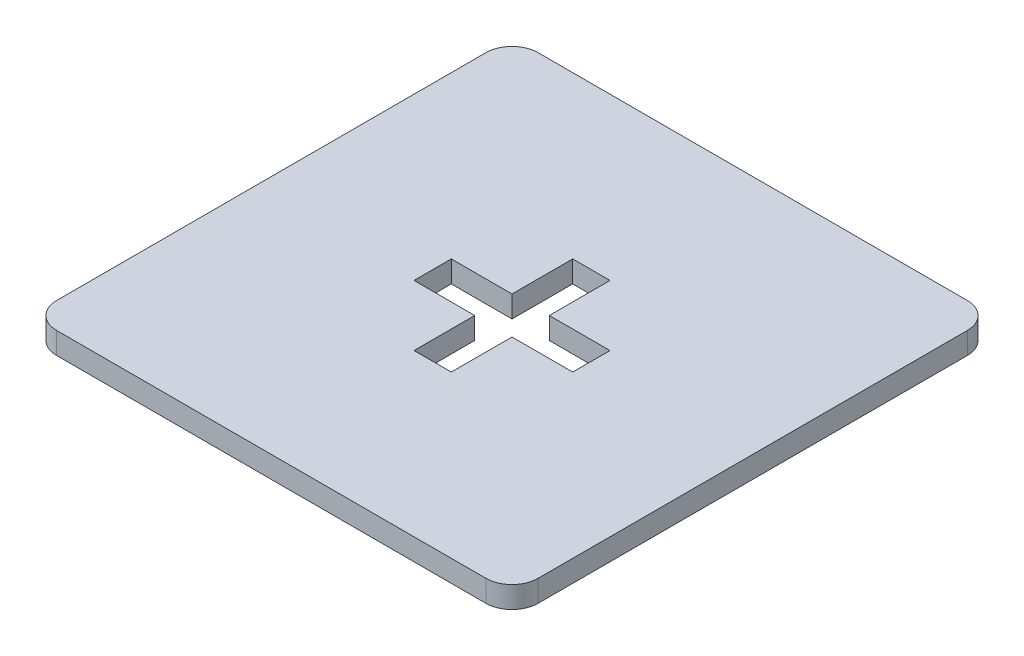
SolidWorks part; units mm, degrees
ref_plane "Plano frontal" through (0, 0, 0) normal (0, 0, 1) x (1, 0, 0)
ref_plane "Plano superior" through (0, 0, 0) normal (0, 1, 0) x (1, 0, 0)
ref_plane "Plano direito" through (0, 0, 0) normal (1, 0, 0) x (0, 0, -1)
sketch "Esboço1" plane through (0, 0, 0) normal (0, 1, 0) x (1, 0, 0)
  line L1 (-27.75, 27.75) -> (27.75, 27.75)
  line L2 (-27.75, 27.75) -> (-27.75, -27.75)
  line L3 (-27.75, -27.75) -> (27.75, -27.75)
  line L4 (27.75, 27.75) -> (27.75, -27.75)
  line L5 (-27.75, 27.75) -> (27.75, -27.75) construction
  line L6 (-27.75, -27.75) -> (27.75, 27.75) construction
  point P0 (0, 0)
  dimension "D1" = 55.5
  dimension "D2" = 55.5
extrude "Ressalto-extrusão1" add sketch "Esboço1" along normal blind 2.5
fillet "Filete1" radius 3 1 edges at (27.75, 1.25, -27.75)
fillet "Filete2" radius 3 1 edges at (-27.75, 1.25, -27.75)
fillet "Filete3" radius 3 1 edges at (-27.75, 1.25, 27.75)
fillet "Filete4" radius 3 1 edges at (27.75, 1.25, 27.75)
sketch "Esboço3" plane through (0, 2.5, 0) normal (0, 1, 0) x (1, 0, 0)
  line L0 (0, 32.1703) -> (0, -31.3347) construction
  line L1 (-34.3986, 0) -> (42.476, 0) construction
  line L3 (-2.15, 9.15) -> (2.15, 9.15)
  line L4 (-2.15, 9.15) -> (-2.15, -9.15)
  line L5 (-2.15, -9.15) -> (2.15, -9.15)
  line L6 (2.15, 9.15) -> (2.15, -9.15)
  line L7 (-2.15, 9.15) -> (2.15, -9.15) construction
  line L8 (-2.15, -9.15) -> (2.15, 9.15) construction
  line L9 (-9.15, 2.15) -> (9.15, 2.15)
  line L10 (-9.15, 2.15) -> (-9.15, -2.15)
  line L11 (-9.15, -2.15) -> (9.15, -2.15)
  line L12 (9.15, 2.15) -> (9.15, -2.15)
  line L13 (-9.15, 2.15) -> (9.15, -2.15) construction
  line L14 (-9.15, -2.15) -> (9.15, 2.15) construction
  point P5 (0, 0)
  point P10 (0, 0)
  dimension "D1" = 4.3
  dimension "D2" = 18.3
  dimension "D3" = 4.3
  dimension "D4" = 18.3
extrude "Corte-extrusão1" cut sketch "Esboço3" against normal through all contours L4 L9 L6 L3 | L10 L11 L4 L9 | L11 L4 L5 L6 | L4 L11 L6 L9 | L12 L9 L6 L11
